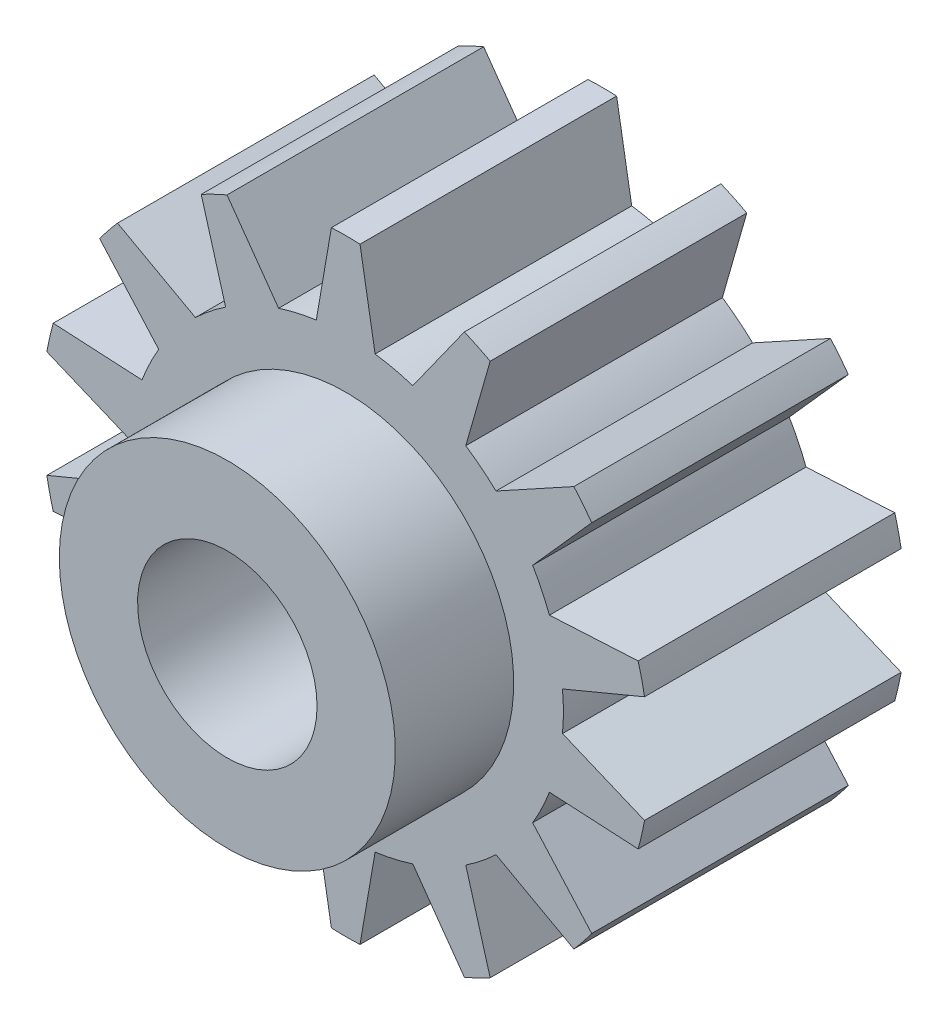
SolidWorks part; units mm, degrees
material "PW50:30:C1:0:1:2:Re:16:"
ref_plane "Plane1" through (0, 0, 0) normal (0, 0, 1) x (1, 0, 0)
ref_plane "Plane2" through (0, 0, 0) normal (0, 1, 0) x (1, 0, 0)
ref_plane "Plane3" through (0, 0, 0) normal (1, 0, 0) x (0, 0, -1)
sketch "Sketch1" plane through (0, 0, 0) normal (0, 0, 1) x (1, 0, 0)
  line L0 (0, 10.9008) -> (0, -10.045) construction
  circle A1 centre (0, 0) radius 5.7
  dimension "D1" = 11.4
extrude "motor gear shape" add sketch "Sketch1" along normal blind 6.72
sketch "Sketch2" plane through (0, 0, 6.72) normal (0, 0, 1) x (1, 0, 0)
  line L0 (0, 9.1728) -> (0, -9.6432) construction
  line L1 (0.375, 7.9412) -> (0.77, 5.6478)
  line L2 (-0.375, 7.9412) -> (-0.77, 5.6478)
  arc A0 (0.375, 7.9412) -> (-0.375, 7.9412) centre (0, 0) ccw
  circle A1 centre (0, 0) radius 5.7 construction
  arc A2 (0.77, 5.6478) -> (-0.77, 5.6478) centre (0, 0) ccw
  dimension "D1" = 15.9
  dimension "D2" = 0.75
  dimension "D3" = 1.54
extrude "motor gear tooth" add sketch "Sketch2" along normal up to surface (6.72 mm away)
pattern_circular "motor gear teeth " count 14 every 25.714 about axis through (0, 0, 0) along (0, 0, 1) of "motor gear tooth"
sketch "Sketch3" plane through (0, 0, 6.72) normal (0, 0, 1) x (1, 0, 0)
  circle A0 centre (0, 0) radius 4.4
  circle A1 centre (0, 0) radius 2.35
  dimension "D1" = 8.8
  dimension "D2" = 4.7
extrude "motor gear boss" add sketch "Sketch3" along normal blind 3.1
sketch "Sketch4" plane through (0, 0, 9.82) normal (0, 0, 1) x (1, 0, 0)
  circle A0 centre (0, 0) radius 2.35 construction
  circle A1 centre (0, 0) radius 2.35
extrude "motor shaft hole" cut sketch "Sketch4" against normal through all
sketch "Sketch5" plane through (0, 0, 0) normal (0, 0, -1) x (-1, 0, 0)
  line L0 (-3.1081, -1.25) -> (3.1081, -1.25)
  circle A2 centre (0, 0) radius 3.35
  arc A3 (-3.1081, -1.25) -> (3.1081, -1.25) centre (0, 0) ccw
  circle A4 centre (0, 0) radius 2.35 construction
  dimension "D1" = 1
  dimension "D2" = 3.6
extrude "motor shaft flat" add sketch "Sketch5" against normal blind 4.9
